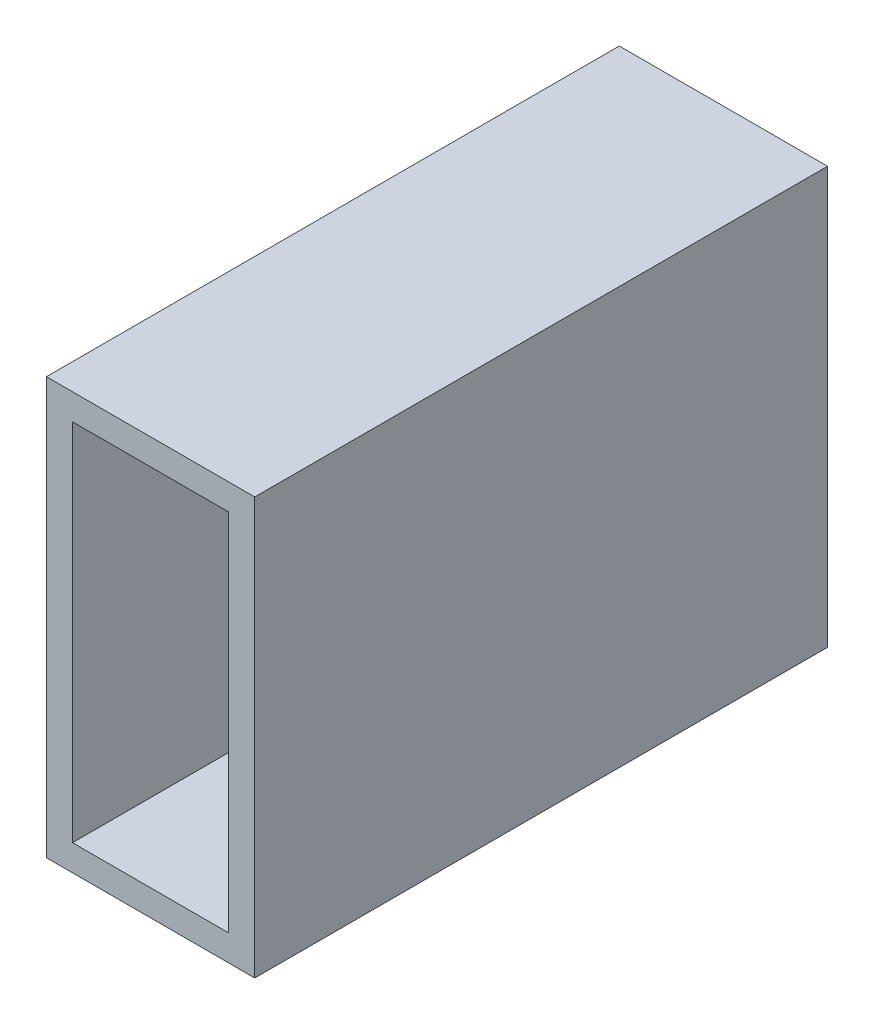
SolidWorks part; units mm, degrees
ref_plane "Front Plane" through (0, 0, 0) normal (0, 0, 1) x (1, 0, 0)
ref_plane "Top Plane" through (0, 0, 0) normal (0, 1, 0) x (1, 0, 0)
ref_plane "Right Plane" through (0, 0, 0) normal (1, 0, 0) x (0, 0, -1)
sketch "Sketch1" plane through (0, 0, 0) normal (0, 0, 1) x (1, 0, 0)
  line L1 (0, 0) -> (25.4, 0)
  line L2 (0, 0) -> (0, 50.8)
  line L3 (0, 50.8) -> (25.4, 50.8)
  line L4 (25.4, 0) -> (25.4, 50.8)
  line L5 (3.175, 3.175) -> (22.225, 3.175)
  line L6 (3.175, 3.175) -> (3.175, 47.625)
  line L7 (3.175, 47.625) -> (22.225, 47.625)
  line L8 (22.225, 3.175) -> (22.225, 47.625)
  dimension "D1" = 50.8
  dimension "D2" = 25.4
  dimension "D3" = 3.175
  dimension "D4" = 3.175
  dimension "D5" = 3.175
  dimension "D6" = 3.175
extrude "Boss-Extrude1" add sketch "Sketch1" along normal blind 69.85
